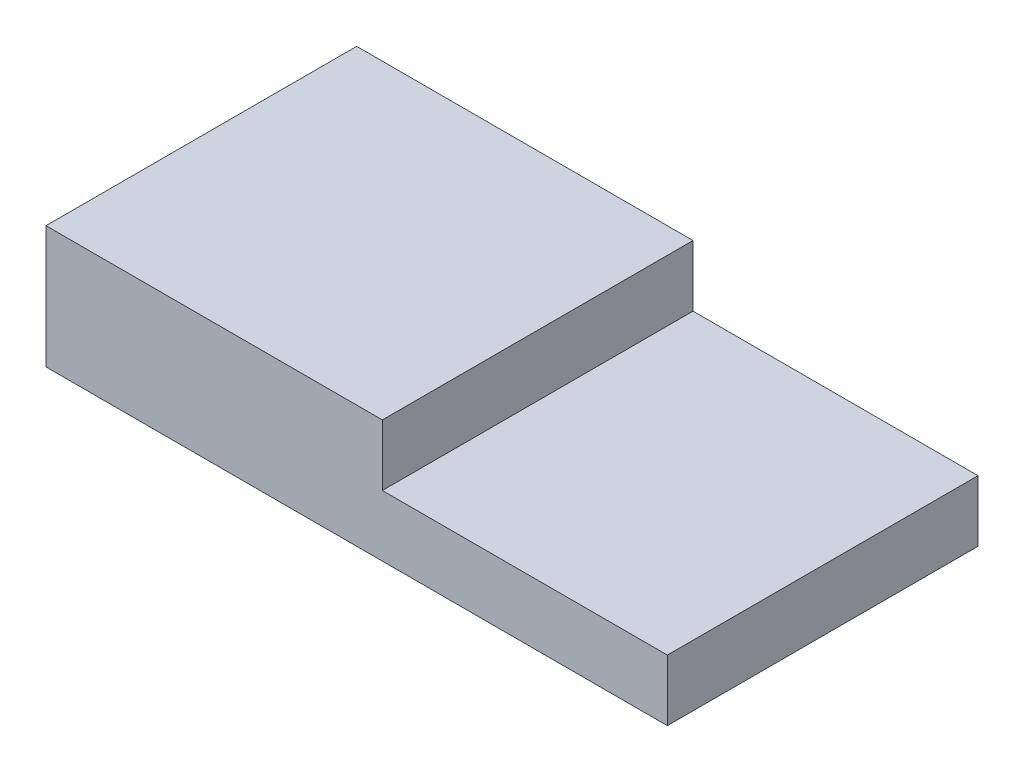
SolidWorks part; units mm, degrees
ref_plane "Front Plane" through (0, 0, 0) normal (0, 0, 1) x (1, 0, 0)
ref_plane "Top Plane" through (0, 0, 0) normal (0, 1, 0) x (1, 0, 0)
ref_plane "Right Plane" through (0, 0, 0) normal (1, 0, 0) x (0, 0, -1)
sketch "Sketch1" plane through (0, 0, 0) normal (0, 1, 0) x (1, 0, 0)
  line L1 (-50.8, -25.4) -> (50.8, -25.4)
  line L2 (-50.8, -25.4) -> (-50.8, 25.4)
  line L3 (-50.8, 25.4) -> (50.8, 25.4)
  line L4 (50.8, -25.4) -> (50.8, 25.4)
  line L5 (0, 25.4) -> (0, -25.4) construction
  point P7 (0, 0)
  dimension "D1" = 101.6
  dimension "D2" = 50.8
extrude "Boss-Extrude1" add sketch "Sketch1" along normal blind 10
sketch "Sketch2" plane through (0, 10, 0) normal (0, 1, 0) x (1, 0, 0)
  line L0 (50.8, 25.4) -> (-50.8, 25.4) construction
  line L1 (-50.8, -25.4) -> (4.2, -25.4)
  line L2 (-50.8, -25.4) -> (-50.8, 25.4)
  line L3 (-50.8, 25.4) -> (4.2, 25.4)
  line L4 (4.2, -25.4) -> (4.2, 25.4)
  dimension "D1" = 55
extrude "Boss-Extrude2" add sketch "Sketch2" along normal blind 10
